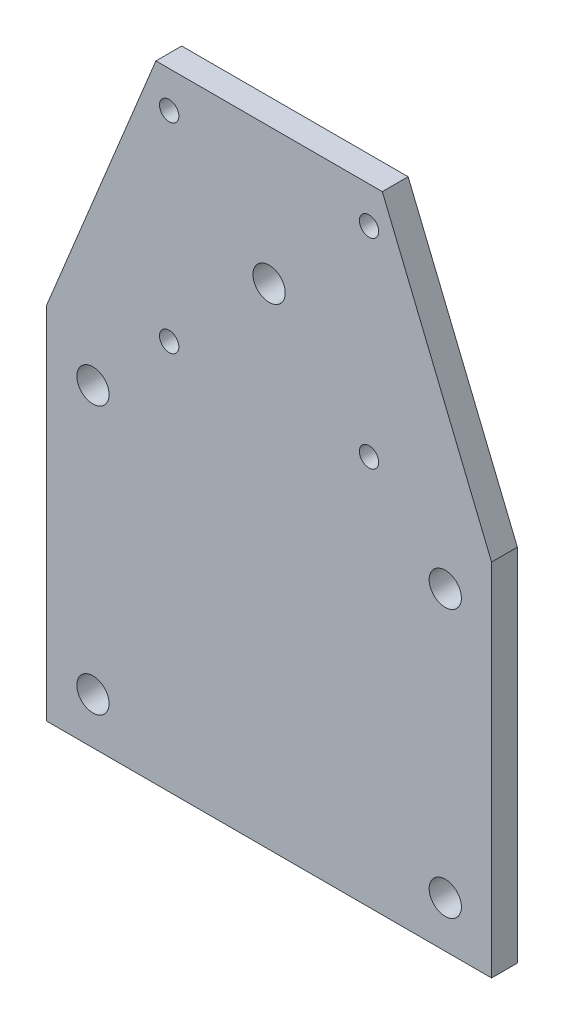
SolidWorks part; units mm, degrees
ref_plane "Front Plane" through (0, 0, 0) normal (0, 0, 1) x (1, 0, 0)
ref_plane "Top Plane" through (0, 0, 0) normal (0, 1, 0) x (1, 0, 0)
ref_plane "Right Plane" through (0, 0, 0) normal (1, 0, 0) x (0, 0, -1)
sketch "Sketch1" plane through (0, 0, 0) normal (0, 0, 1) x (1, 0, 0)
  line L0 (-21.15, 9.85) -> (-9.85, 21.15)
  line L1 (-21.15, -21.15) -> (21.15, -21.15)
  line L2 (-21.15, -21.15) -> (-21.15, 21.15)
  line L3 (-21.15, 21.15) -> (21.15, 21.15)
  line L4 (21.15, -21.15) -> (21.15, 21.15)
  line L5 (-21.15, -21.15) -> (21.15, 21.15) construction
  line L6 (-21.15, 21.15) -> (21.15, -21.15) construction
  line L7 (0, 21.15) -> (0, -21.15) construction
  line L8 (-21.15, 0) -> (21.15, 0) construction
  line L9 (21.15, 9.85) -> (9.85, 21.15)
  line L10 (21.15, -9.85) -> (9.85, -21.15)
  line L11 (-21.15, -9.85) -> (-9.85, -21.15)
  line L12 (-21.15, 17.5579) -> (-17.5579, 21.15)
  line L13 (21.15, 17.5579) -> (17.5579, 21.15)
  line L14 (21.15, -17.5579) -> (17.5579, -21.15)
  line L15 (-21.15, -17.5579) -> (-17.5579, -21.15)
  circle A0 centre (-15.5, 15.5) radius 1.5
  circle A1 centre (15.5, 15.5) radius 1.5
  circle A2 centre (15.5, -15.5) radius 1.5
  circle A3 centre (-15.5, -15.5) radius 1.5
  circle A4 centre (0, 0) radius 2.5
  point P0 (0, 0)
  point P14 (-15.5, 15.5)
  point P15 (15.5, 15.5)
  point P32 (-19.3539, 19.3539)
  dimension "D3" = 3
  dimension "D5" = 5
  dimension "D1" = 42.3
  dimension "D2" = 31
  dimension "D4" = 2.54
sketch "Sketch3" plane through (0, 0, 0) normal (0, 0, 1) x (1, 0, 0)
  line L0 (0, 0) -> (-27.3205, -27.3205) construction
  line L1 (0, 21.15) -> (0, -21.15) construction
  line L2 (0, 21.15) -> (0, -21.15) construction
  line L3 (0, 0) -> (27.3205, -27.3205) construction
  line L4 (-21.15, -21.15) -> (21.15, 21.15) construction
  line L5 (-27.3205, -27.3205) -> (-27.3205, -68.8205) construction
  line L6 (27.3205, -27.3205) -> (27.3205, -68.8205) construction
  line L7 (-27.3205, -48.0705) -> (27.3205, -48.0705) construction
  line L8 (-27.3205, -39.3205) -> (27.3205, -39.3205) construction
  line L9 (-27.3205, -39.3205) -> (0, 8) construction
  circle A1 centre (-27.3205, -27.3205) radius 12
  circle A2 centre (27.3205, -27.3205) radius 12
  circle A3 centre (27.3205, -68.8205) radius 12
  circle A4 centre (-27.3205, -68.8205) radius 12
  circle A5 centre (0, 0) radius 4
  circle A6 centre (0, 0) radius 8
  circle A7 centre (-27.3205, -27.3205) radius 2.5
  circle A8 centre (-27.3205, -68.8205) radius 2.5
  point P19 (-27.3205, -56.8205)
  point P22 (-27.3205, -15.3205)
  point P23 (-27.3205, -80.8205)
  point P26 (-27.3205, -24.8205)
  point P27 (-27.3205, -29.8205)
  point P28 (-27.3205, -71.3205)
  point P29 (-27.3205, -66.3205)
  dimension "D1" = 24
  dimension "D3" = 8
  dimension "D4" = 16
  dimension "D7" = 5
  dimension "D2" = 41.5
  dimension "D5" = 60
  dimension "D6" = 65.5
  dimension "D8" = 46.5
  dimension "D9" = 36.5
sketch "Sketch4" plane through (0, 0, 0) normal (0, 0, 1) x (1, 0, 0)
  line L0 (0, 21.15) -> (0, -21.15) construction
  line L1 (0, 21.15) -> (0, -21.15) construction
  line L2 (-27.3205, -48.0705) -> (27.3205, -48.0705) construction
  line L3 (-27.3205, -48.0705) -> (27.3205, -48.0705) construction
  line L4 (-34.5047, -20.1363) -> (-27.3205, -27.3205)
  line L5 (-34.5047, -20.1363) -> (34.5047, -20.1363)
  line L6 (-34.5047, -20.1363) -> (-34.5047, -76.0047)
  line L7 (-34.5047, -76.0047) -> (34.5047, -76.0047)
  line L8 (34.5047, -20.1363) -> (34.5047, -76.0047)
  line L9 (-27.3205, -27.3205) -> (-34.5047, -27.3205) construction
  line L10 (34.5047, -20.1363) -> (27.3205, -27.3205)
  line L11 (34.5047, -76.0047) -> (27.3205, -68.8205)
  line L12 (-34.5047, -76.0047) -> (-27.3205, -68.8205)
  line L13 (-34.5047, -20.1363) -> (-17.5579, 21.15)
  line L14 (-17.5579, 21.15) -> (17.5579, 21.15)
  line L15 (17.5579, 21.15) -> (34.5047, -20.1363)
  circle A0 centre (-27.3205, -27.3205) radius 2.5
  circle A1 centre (27.3205, -27.3205) radius 2.5
  circle A2 centre (27.3205, -68.8205) radius 2.5
  circle A3 centre (-27.3205, -68.8205) radius 2.5
  circle A4 centre (-15.5, -15.5) radius 1.5 construction
  circle A5 centre (-15.5, -15.5) radius 1.5
  circle A6 centre (-15.5, 15.5) radius 1.5 construction
  circle A7 centre (-15.5, 15.5) radius 1.5
  circle A8 centre (15.5, 15.5) radius 1.5 construction
  circle A9 centre (15.5, 15.5) radius 1.5
  circle A10 centre (15.5, -15.5) radius 1.5 construction
  circle A11 centre (15.5, -15.5) radius 1.5
  circle A12 centre (0, 0) radius 2.5 construction
  circle A13 centre (0, 0) radius 2.5
  dimension "D1" = 5
  dimension "D2" = 45
  dimension "D3" = 10.16
  dimension "D4" = 41.5
extrude "Boss-Extrude1" add sketch "Sketch4" along normal blind 4
ref_plane "Plane1" through (0, -48.0705, 0) normal (0, 1, 0) x (1, 0, 0)
sketch "Sketch5" plane through (0, 0, 4) normal (0, 0, 1) x (1, 0, 0)
  line L0 (0, 0) -> (0, 50000) construction
  line L1 (-27.3205, -27.3205) -> (-27.3205, -68.8205) construction
  line L2 (-1027.3205, -48.0705) -> (48972.6795, -48.0705) construction
  line L3 (-27.3205, -27.3205) -> (27.3205, -27.3205) construction
  line L4 (-27.3205, -68.8205) -> (27.3205, -68.8205) construction
  circle A2 centre (0, -68.8205) radius 2
  circle A3 centre (0, -55.3538) radius 2
  circle A4 centre (0, -41.8871) radius 2
  circle A5 centre (0, -28.4204) radius 2
  point P10 (-27.3205, -48.0705)
  dimension "D1" = 4
  dimension "D2" = 4
extrude "Cut-Extrude1" [suppressed] cut sketch "Sketch5" against normal blind 10
sketch "Sketch6" [suppressed] plane through (0, 0, 4) normal (0, 0, 1) x (1, 0, 0)
  line L0 (30.0526, -48.0705) -> (-30.0526, -48.0705) construction
  line L1 (-34.5047, -76.0047) -> (34.5047, -76.0047) construction
  line L2 (-17.5579, 21.15) -> (17.5579, 21.15) construction
  line L3 (-34.5047, -76.0047) -> (34.5047, -76.0047)
  line L4 (-17.5579, 21.15) -> (17.5579, 21.15)
  line L5 (0, 21.15) -> (0, -76.0047) construction
  circle A0 centre (0, -48.0705) radius 2.5
  dimension "D1" = 5
extrude "Cut-Extrude2" [suppressed] cut sketch "Sketch6" against normal up to surface and the other way through all contours A0 L5 | L5 A0
sketch "Sketch7" [suppressed] plane through (0, 0, 4) normal (0, 0, 1) x (1, 0, 0)
  line L0 (0, 21.15) -> (0, -76.0047) construction
  line L1 (0, 21.15) -> (0, -76.0047) construction
  circle A0 centre (0, -68.0705) radius 2.5
  circle A1 centre (0, -48.0705) radius 2.5 construction
  circle A2 centre (0, -48.0705) radius 2.5 construction
  dimension "D1" = 20
extrude "Cut-Extrude3" [suppressed] cut sketch "Sketch7" against normal blind 10
sketch "Sketch8" [suppressed] plane through (0, 0, 4) normal (0, 0, 1) x (1, 0, 0)
  line L0 (-34.5047, -48.0705) -> (34.5047, -48.0705) construction
  line L1 (-24.8205, -68.8205) -> (-24.8205, -27.3205) construction
  line L2 (-4.8205, -58.0705) -> (-24.8205, -58.0705)
  line L3 (-4.8205, -58.0705) -> (-4.8205, -38.0705)
  line L4 (-4.8205, -38.0705) -> (-24.8205, -38.0705)
  line L5 (-24.8205, -58.0705) -> (-24.8205, -38.0705)
  line L6 (-34.5047, -20.1363) -> (-34.5047, -76.0047)
  line L7 (-34.5047, -76.0047) -> (34.5047, -76.0047)
  line L8 (34.5047, -76.0047) -> (34.5047, -20.1363)
  line L9 (34.5047, -20.1363) -> (17.5579, 21.15)
  line L10 (17.5579, 21.15) -> (-17.5579, 21.15)
  line L11 (-17.5579, 21.15) -> (-34.5047, -20.1363)
  line L12 (-34.5047, -20.1363) -> (-34.5047, -76.0047)
  line L13 (-34.5047, -76.0047) -> (34.5047, -76.0047)
  line L14 (34.5047, -76.0047) -> (34.5047, -20.1363)
  line L15 (34.5047, -20.1363) -> (17.5579, 21.15)
  line L16 (17.5579, 21.15) -> (-17.5579, 21.15)
  line L17 (-17.5579, 21.15) -> (-34.5047, -20.1363)
  line L18 (-4.8205, -58.0705) -> (-24.8205, -38.0705) construction
  line L19 (-4.8205, -38.0705) -> (-24.8205, -58.0705) construction
  line L20 (0, 21.15) -> (0, -76.0047) construction
  line L21 (4.8205, -38.0705) -> (24.8205, -38.0705)
  line L22 (24.8205, -58.0705) -> (24.8205, -38.0705)
  line L23 (4.8205, -58.0705) -> (24.8205, -58.0705)
  line L24 (4.8205, -58.0705) -> (4.8205, -38.0705)
  line L25 (4.8205, -38.0705) -> (24.8205, -58.0705) construction
  line L26 (4.8205, -58.0705) -> (24.8205, -38.0705) construction
  circle A0 centre (-27.3205, -68.8205) radius 2.5 construction
  circle A1 centre (-27.3205, -27.3205) radius 2.5 construction
  circle A2 centre (-27.3205, -68.8205) radius 2.5
  circle A3 centre (-27.3205, -27.3205) radius 2.5
  circle A4 centre (-19.5172, -52.7672) radius 2.5
  circle A5 centre (-10.1238, -43.3738) radius 2.5
  circle A6 centre (10.1238, -43.3738) radius 2.5
  circle A7 centre (19.5172, -52.7672) radius 2.5 construction
  circle A8 centre (19.5172, -43.3738) radius 2.5
  circle A9 centre (10.1238, -52.7672) radius 2.5 construction
  point P6 (-14.8205, -48.0705)
  dimension "D3" = 5
  dimension "D2" = 20
  dimension "D4" = 7.5
  dimension "D1" = 0
extrude "Cut-Extrude4" [suppressed] cut sketch "Sketch8" against normal through all contours A5 | A9 | A8 | A6 | A7 | A4
